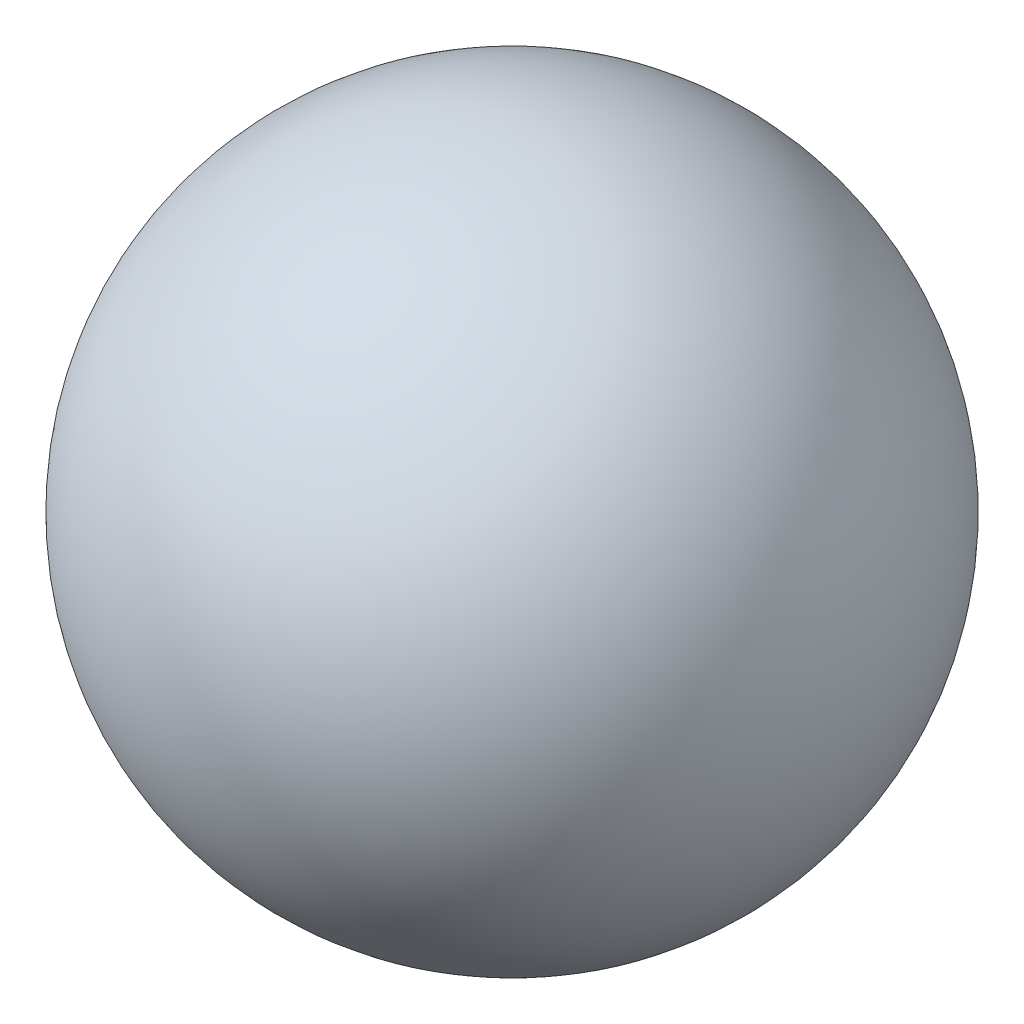
SolidWorks part; units mm, degrees
ref_plane "Front Plane" through (0, 0, 0) normal (0, 0, 1) x (1, 0, 0)
ref_plane "Top Plane" through (0, 0, 0) normal (0, 1, 0) x (1, 0, 0)
ref_plane "Right Plane" through (0, 0, 0) normal (1, 0, 0) x (0, 0, -1)
sketch "Sketch2" plane through (0, 0, 0) normal (0, 0, 1) x (1, 0, 0)
  line L0 (0, 1.143) -> (0, -1.143)
  arc A0 (0, 1.143) -> (0, -1.143) centre (0, 0) cw
  dimension "D1" = 2.286
revolve "Revolve1" add sketch "Sketch2" angle 360 about L0
sketch "Sketch3" plane through (0, 0, 0) normal (0, 1, 0) x (1, 0, 0)
  line L0 (0, 0) -> (0, -4.953) construction
  dimension "D1" = 4.953
sketch "Sketch4" plane through (0, 0, 0) normal (1, 0, 0) x (0, 0, -1)
  line L0 (-4.953, 1.143) -> (-4.953, -1.143) construction
  line L1 (0, 0) -> (-4.953, 0) construction
  point P0 (-4.953, 0)
  point P3 (-4.953, 0)
  point P6 (-4.953, 0)
  point P7 (0, 0)
  dimension "D1" = 2.286
  dimension "D2" = 4.953
